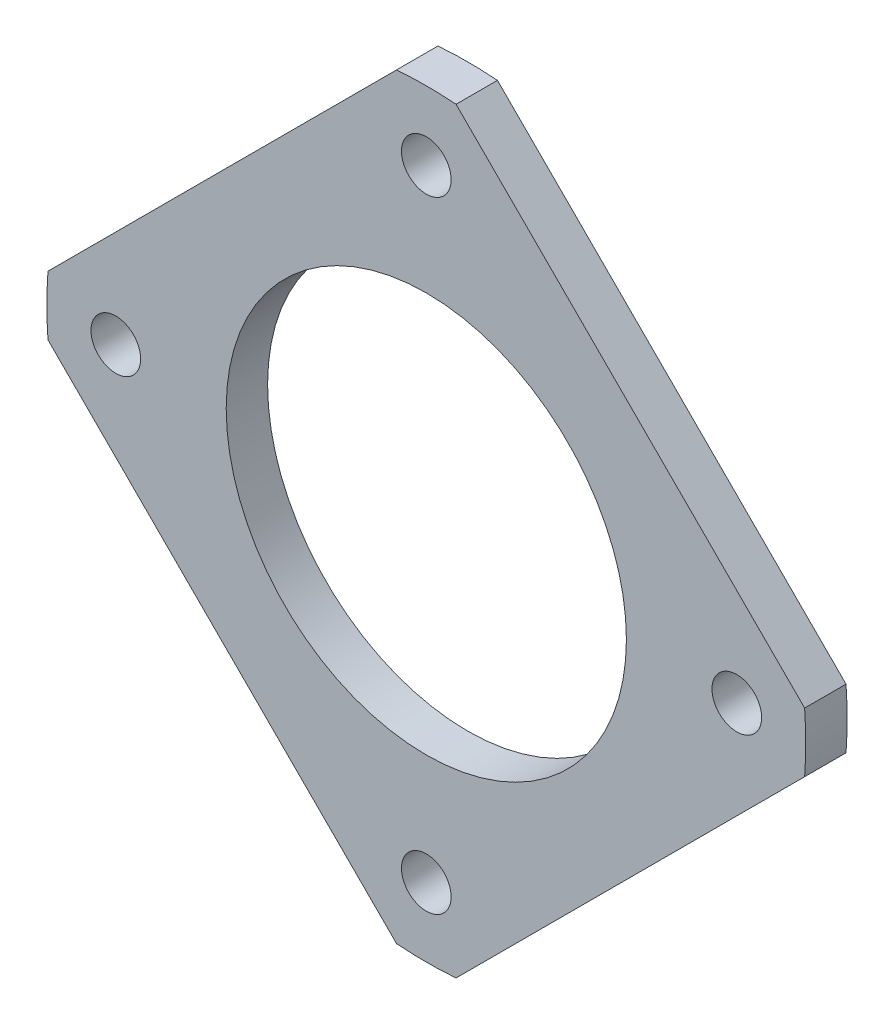
SolidWorks part; units mm, degrees
ref_plane "Front Plane" through (0, 0, 0) normal (0, 0, 1) x (1, 0, 0)
ref_plane "Top Plane" through (0, 0, 0) normal (0, 1, 0) x (1, 0, 0)
ref_plane "Right Plane" through (0, 0, 0) normal (1, 0, 0) x (0, 0, -1)
sketch "Sketch1" plane through (0, 0, 0) normal (0, 0, 1) x (1, 0, 0)
  circle A0 centre (0, 0) radius 14.5
  circle A1 centre (0, 0) radius 27.5
  circle A2 centre (0, 0) radius 22.5 construction
  circle A3 centre (0, 22.5) radius 1.5
  circle A4 centre (22.5, 0) radius 1.5
  circle A5 centre (0, -22.5) radius 1.5
  circle A6 centre (-22.5, 0) radius 1.5
  point P16 (0, 0)
  dimension "D1" = 29
  dimension "D2" = 55
  dimension "D3" = 45
  dimension "D4" = 3
  dimension "D5" = 4
extrude "Boss-Extrude1" add sketch "Sketch1" along normal blind 3
sketch "Sketch2" plane through (0, 0, 3) normal (0, 0, 1) x (1, 0, 0)
  line L0 (-29.5711, 0) -> (0, 29.5711)
  line L1 (0, 29.5711) -> (29.5711, 0)
  line L2 (29.5711, 0) -> (0, -29.5711)
  line L3 (0, -29.5711) -> (-29.5711, 0)
  circle A0 centre (-22.5, 0) radius 5 construction
  circle A1 centre (0, 22.5) radius 5 construction
  circle A2 centre (0, 0) radius 27.5 construction
  circle A3 centre (0, -22.5) radius 5 construction
  circle A5 centre (0, 0) radius 27.5
  circle A6 centre (0, 0) radius 27.5
  circle M11 centre (0, 0) radius 27.5
  dimension "D1" = 0
extrude "Cut-Extrude1" cut sketch "Sketch2" against normal blind 10 contours L0 M11 | L1 M11 | L2 M11 | L3 M11
hole_wizard "M3 Clearance Hole1" positions "Sketch3" profile "Sketch4" hole size "M3" standard "DIN" end condition through all
sketch "Sketch3" plane through (0, 0, 3) normal (0, 0, 1) x (1, 0, 0)
  point P0 (0, 22.5)
  point P3 (-22.5, 0)
  point P6 (0, -22.5)
  point P9 (22.5, 0)
sketch "Sketch4" plane through (0, 22.5, 3) normal (1, 0, 0) x (0, -1, 0)
  line L0 (0, 0) -> (0, 3)
  line L1 (0, 3) -> (1.8, 3)
  line L2 (1.8, 3) -> (1.8, 0)
  line L5 (1.8, 0) -> (0, 0)
  line L11 (0, -6.35) -> (0, 107.95) construction
  dimension "Thru Hole Dia." = 3.6
  dimension "Thru Hole Depth" = 3
